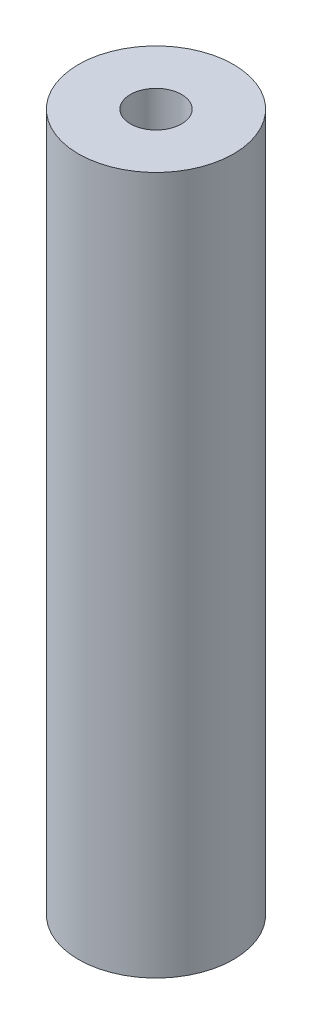
SolidWorks part; units mm, degrees
material "5052-H34"
ref_plane "正面" through (0, 0, 0) normal (0, 0, 1) x (1, 0, 0)
ref_plane "平面" through (0, 0, 0) normal (0, 1, 0) x (1, 0, 0)
ref_plane "右側面" through (0, 0, 0) normal (1, 0, 0) x (0, 0, -1)
sketch "ｽｹｯﾁ1" plane through (0, 0, 0) normal (0, 1, 0) x (1, 0, 0)
  circle A0 centre (0, 0) radius 5
  dimension "D1" = 10
extrude "ﾎﾞｽ - 押し出し1" add sketch "ｽｹｯﾁ1" along normal blind 45
hole_wizard "M4x0.7 ねじ穴1" positions "ｽｹｯﾁ2" profile "ｽｹｯﾁ3" tap size "M4x0.7" standard "JIS"
sketch "ｽｹｯﾁ2" plane through (0, 45, 0) normal (0, 1, 0) x (1, 0, 0)
  point P0 (0, 0)
sketch "ｽｹｯﾁ3" plane through (0, 45, 0) normal (1, 0, 0) x (0, 0, 1)
  line L0 (0, 0) -> (0, 15.9914)
  line L1 (0, 15.9914) -> (1.65, 15)
  line L2 (1.65, 15) -> (1.65, 0)
  line L5 (1.65, 0) -> (0, 0)
  line L10 (0, 15.9914) -> (-1.65, 15) construction
  line L11 (0, -6.35) -> (0, 107.95) construction
  dimension "ねじ下穴ﾄﾞﾘﾙ直径" = 3.3
  dimension "ねじ下穴ﾄﾞﾘﾙの深さ" = 15
  dimension "ﾄﾞﾘﾙ角度" = 118
ref_plane "平面1" through (0, 22.5, 0) normal (0, 1, 0) x (1, 0, 0)
mirror "ﾐﾗｰ1" about plane through (0, 22.5, 0) normal (0, 1, 0) of "M4x0.7 ねじ穴1"
